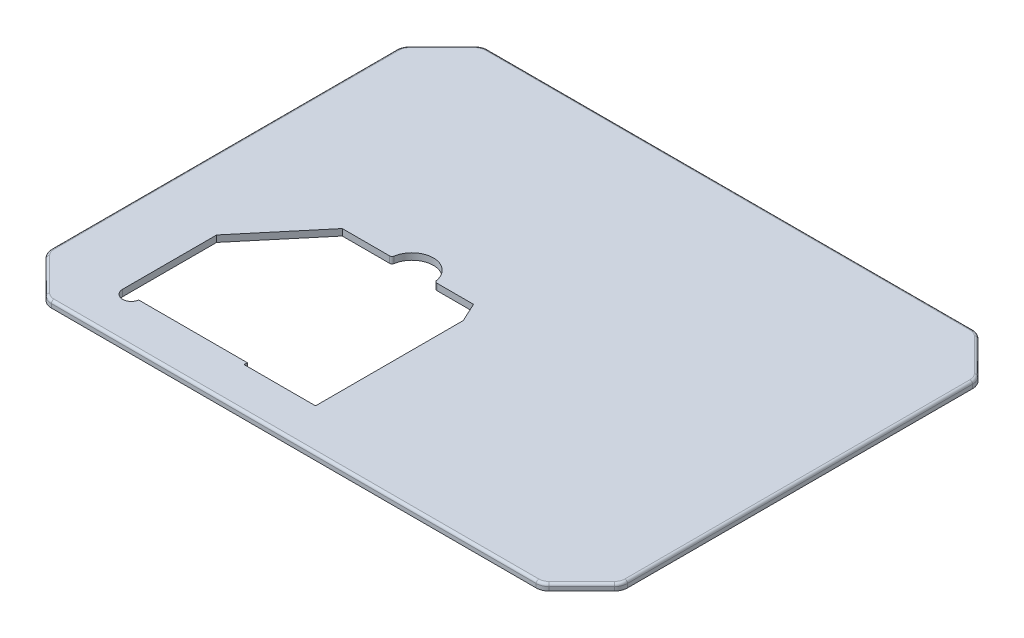
SolidWorks part; units mm, degrees
ref_plane "Front Plane" through (0, 0, 0) normal (0, 0, 1) x (1, 0, 0)
ref_plane "Top Plane" through (0, 0, 0) normal (0, 1, 0) x (1, 0, 0)
ref_plane "Right Plane" through (0, 0, 0) normal (1, 0, 0) x (0, 0, -1)
sketch "Sketch1" plane through (0, 0, 0) normal (0, 1, 0) x (1, 0, 0)
  line L5 (8.475, 41.375) -> (8.475, -41.375) construction
  line L11 (-18.594, 20.625) -> (31.365, 20.625) construction
  line L12 (-58.375, 109.125) -> (143.375, 109.125)
  line L13 (-68.375, 99.125) -> (-68.375, -48.875)
  line L14 (-58.375, -58.875) -> (143.375, -58.875)
  line L15 (153.375, 99.125) -> (153.375, -48.875)
  line L19 (0, 109.125) -> (0, -58.875) construction
  line L20 (-52.875, 109.125) -> (-68.375, 93.625)
  line L21 (42.5, 109.125) -> (42.5, -58.875) construction
  line L24 (27.2851, 29.3853) -> (34.625, 13.625)
  line L25 (34.625, 13.625) -> (34.625, -41.375)
  line L28 (35.125, -41.875) -> (-34.1622, -41.875)
  line L32 (-40.375, -5.375) -> (-7.4311, 33.9501)
  line L33 (-40.375, -41.375) -> (-40.375, -5.375)
  line L34 (34.625, -41.375) -> (-34.625, -41.375)
  line L35 (-40.875, -41.375) -> (-40.875, -5.1932)
  line L36 (137.875, 109.125) -> (153.375, 93.625)
  line L37 (153.375, 25.125) -> (-68.375, 25.125) construction
  line L38 (137.875, -58.875) -> (153.375, -43.375)
  line L39 (-52.875, -58.875) -> (-68.375, -43.375)
  line L40 (-40.875, -5.1932) -> (-7.8144, 34.2712)
  line L41 (27.7384, 29.5964) -> (35.125, 13.7357)
  line L42 (35.125, 13.7357) -> (35.125, -41.875)
  line L43 (7.625, -41.875) -> (7.625, -43.125)
  line L44 (7.625, -43.125) -> (35.125, -43.125)
  line L45 (35.125, -43.125) -> (35.125, -41.875)
  line L46 (-18.8274, 21.125) -> (31.6837, 21.125)
  arc A8 (-40.375, -41.375) -> (-34.625, -41.375) centre (-37.5, -41.375) ccw
  arc A11 (-7.4311, 33.9501) -> (27.2851, 29.3853) centre (8.475, 20.625) cw
  arc A14 (-68.375, -48.875) -> (-58.375, -58.875) centre (-58.375, -48.875) ccw construction
  arc A15 (143.375, -58.875) -> (153.375, -48.875) centre (143.375, -48.875) ccw construction
  arc A16 (143.375, 109.125) -> (153.375, 99.125) centre (143.375, 99.125) cw construction
  arc A17 (-58.375, 109.125) -> (-68.375, 99.125) centre (-58.375, 99.125) ccw construction
  arc A18 (-40.875, -41.375) -> (-34.1622, -41.875) centre (-37.5, -41.375) ccw
  arc A19 (-7.8144, 34.2712) -> (27.7384, 29.5964) centre (8.475, 20.625) cw
  arc A20 (-7.8144, 34.2712) -> (27.7384, 29.5964) centre (8.475, 20.625) cw construction
  arc A21 (16.725, 20.625) -> (0.225, 20.625) centre (8.475, 20.625) ccw
  point P2 (0, -41.375)
  point P4 (8.475, 0)
  point P7 (-68.375, -58.875)
  point P25 (0, 0)
  point P28 (153.375, 109.125)
  point P33 (-68.375, 109.125)
  dimension "D6" = 48.85
  dimension "D7" = 36
  dimension "D10" = 0.5
  dimension "D9" = 168
  dimension "D13" = 27.5
  dimension "D4" = 55
  dimension "D5" = 62
  dimension "D8" = 82.75
  dimension "D15" = 28
  dimension "D16" = 10
  dimension "D17" = 5.5
  dimension "D19" = 16.5
  dimension "D2" = 75
  dimension "D3" = 5.75
  dimension "D11" = 221.75
  dimension "D12" = 17.5
  dimension "D14" = 1.25
  dimension "D18" = 5.5
  dimension "D20" = 0.5
extrude "Boss-Extrude1" add sketch "Sketch1" along normal blind 2.5
fillet "Fillet2" radius 5 8 edges at (-68.375, 1.25, -93.625) (-52.875, 1.25, -109.125) (153.375, 1.25, -93.625) (137.875, 1.25, -109.125) (153.375, 1.25, 43.375) (137.875, 1.25, 58.875) (-52.875, 1.25, 58.875) (-68.375, 1.25, 43.375)
fillet "Fillet3" radius 1 18 edges at (-52.7173, 2.5, -108.7444) (42.5, 2.5, -109.125) (137.7173, 2.5, -108.7444) (145.625, 2.5, -101.375) (152.9944, 2.5, -93.4673) (153.375, 2.5, -25.125) (152.9944, 2.5, 43.2173) (145.625, 2.5, 51.125) (137.7173, 2.5, 58.4944) (-52.7173, 2.5, 58.4944) (-60.625, 2.5, 51.125) (-67.9944, 2.5, 43.2173) (-68.375, 2.5, -25.125) (-67.9944, 2.5, -93.4673) (-60.625, 2.5, -101.375) (42.5, 2.5, 58.875) (16.7098, 1.25, -21.125) (0.2402, 1.25, -21.125)
